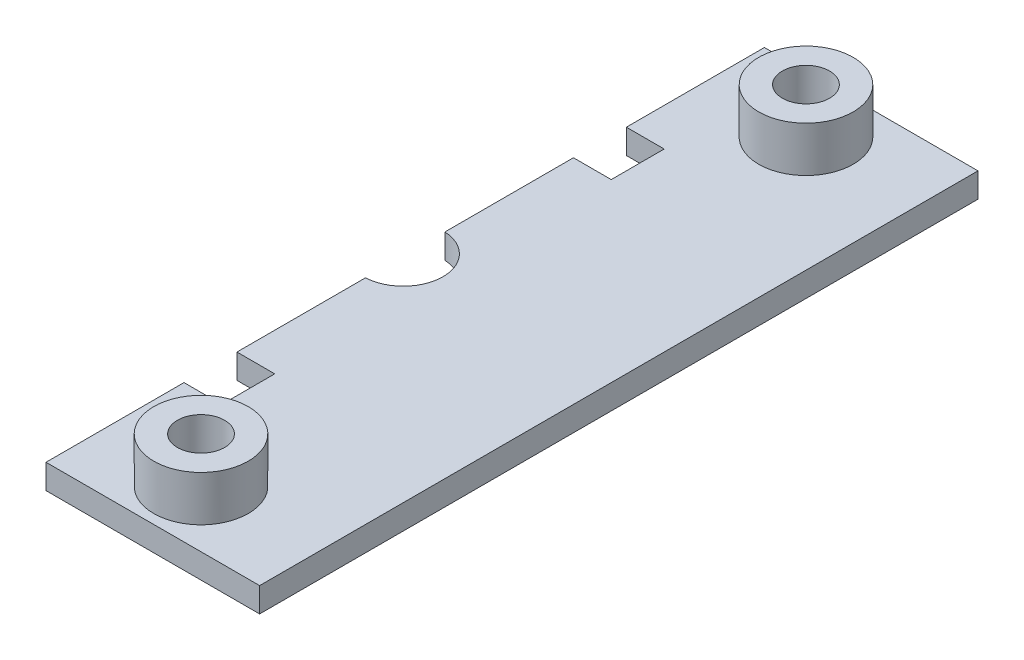
SolidWorks part; units mm, degrees
material "ABS"
ref_plane "Front Plane" through (0, 0, 0) normal (0, 0, 1) x (1, 0, 0)
ref_plane "Top Plane" through (0, 0, 0) normal (0, 1, 0) x (1, 0, 0)
ref_plane "Right Plane" through (0, 0, 0) normal (1, 0, 0) x (0, 0, -1)
sketch "Sketch1" plane through (0, 0, 0) normal (0, 1, 0) x (1, 0, 0)
  line L1 (-5.65, 19) -> (5.65, 19)
  line L2 (-5.65, 19) -> (-5.65, -19)
  line L3 (-5.65, -19) -> (5.65, -19)
  line L4 (5.65, 19) -> (5.65, -19)
  line L5 (-5.65, 19) -> (5.65, -19) construction
  line L6 (-5.65, -19) -> (5.65, 19) construction
  point P0 (0, 0)
  dimension "D1" = 11.3
  dimension "D2" = 38
extrude "BASE" add sketch "Sketch1" along normal blind 1.3
sketch "Sketch3" plane through (0, 1.3, 0) normal (0, 1, 0) x (1, 0, 0)
  line L0 (-5.65, 19) -> (-5.65, -19) construction
  line L1 (-5.65, 11.7) -> (-3.65, 11.7)
  line L2 (-5.65, 11.7) -> (-5.65, 8.9)
  line L3 (-5.65, 8.9) -> (-3.65, 8.9)
  line L4 (-3.65, 11.7) -> (-3.65, 8.9)
  dimension "D1" = 2
  dimension "D2" = 2.8
  dimension "D3" = 11.7
extrude "SQUARE NOTCH" cut sketch "Sketch3" against normal through all
mirror "SN Mirror1" about plane through (0, 0, 0) normal (0, 0, 1) of "SQUARE NOTCH"
sketch "Sketch2" plane through (0, 1.3, 0) normal (0, 1, 0) x (1, 0, 0)
  line L0 (-3.65, 8.9) -> (-3.65, 11.7) construction
  line L1 (-3.65, 0) -> (-5.65, 0) construction
  line L2 (-5.65, 8.9) -> (-5.65, -8.9) construction
  line L3 (-5.65, -2.1) -> (-5.65, 2.1) construction
  circle A0 centre (-5.7525, 0) radius 2.1025
  dimension "D1" = 4.2
extrude "CIRCLE" cut sketch "Sketch2" against normal through all
sketch "Sketch4" plane through (0, 1.3, 0) normal (0, 1, 0) x (1, 0, 0)
  line L0 (-5.65, 19) -> (-5.65, 11.7) construction
  line L1 (5.65, 19) -> (-5.65, 19) construction
  circle A0 centre (-0.45, 16) radius 2.5
  circle A1 centre (-0.45, 16) radius 1.25
  dimension "D1" = 2.5
  dimension "D2" = 5
  dimension "D3" = 3
  dimension "D4" = 5.2
  dimension "D5" = 16
extrude "BOSSED CYLINDER WITH HOLE" add sketch "Sketch4" along normal blind 2.4
mirror "BCH Mirror2" about plane through (0, 0, 0) normal (0, 0, 1) of "BOSSED CYLINDER WITH HOLE"
